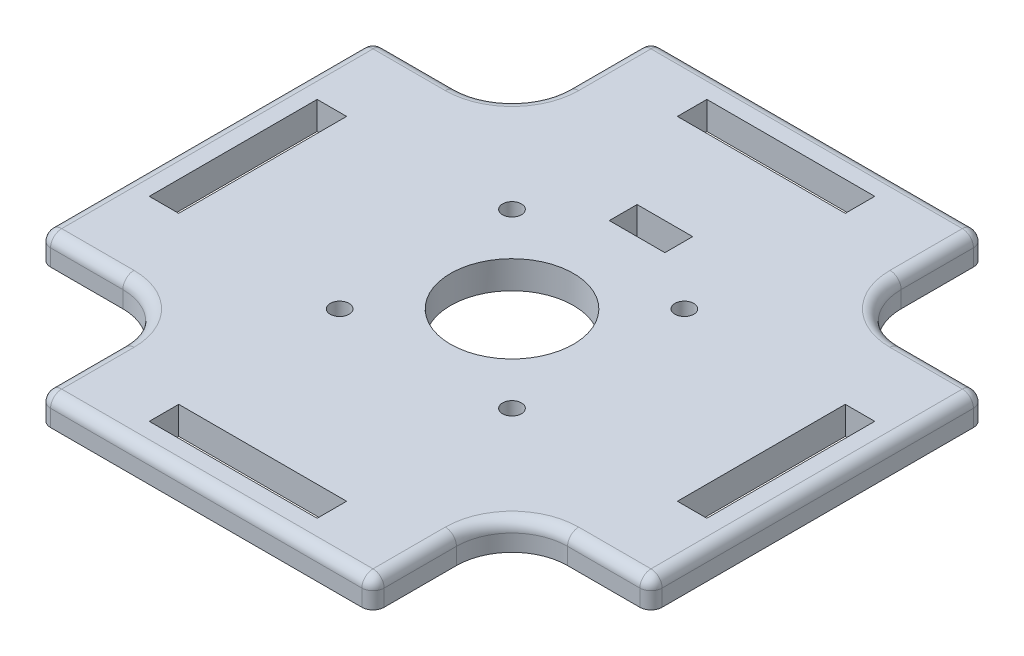
SolidWorks part; units mm, degrees
ref_plane "Płaszczyzna przednia" through (0, 0, 0) normal (0, 0, 1) x (1, 0, 0)
ref_plane "Płaszczyzna górna" through (0, 0, 0) normal (0, 1, 0) x (1, 0, 0)
ref_plane "Płaszczyzna prawa" through (0, 0, 0) normal (1, 0, 0) x (0, 0, -1)
sketch "Sketch1" plane through (0, 0, 0) normal (0, 1, 0) x (1, 0, 0)
  line L0 (-30, 55) -> (30, 55)
  line L1 (30, 55) -> (30, 30)
  line L2 (30, 30) -> (55, 30)
  line L3 (55, 30) -> (55, -30)
  line L4 (55, -30) -> (30, -30)
  line L5 (30, -30) -> (30, -55)
  line L6 (30, -55) -> (-30, -55)
  line L7 (-30, -55) -> (-30, -30)
  line L8 (-30, -30) -> (-55, -30)
  line L9 (-55, -30) -> (-55, 30)
  line L10 (-55, 30) -> (-30, 30)
  line L11 (-30, 30) -> (-30, 55)
  line L12 (0, 55) -> (0, -55) construction
  line L13 (-55, 0) -> (55, 0) construction
  point P14 (0, 0)
  point P18 (0, 0)
  dimension "D1" = 60
  dimension "D2" = 110
  dimension "D3" = 110
  dimension "D4" = 60
extrude "Boss-Extrude1" add sketch "Sketch1" along normal blind 5
sketch "Sketch2" plane through (0, 5, 0) normal (0, 1, 0) x (1, 0, 0)
  line L0 (-55, 0) -> (55, 0) construction
  line L1 (-55, 30) -> (-55, -30) construction
  line L2 (55, -30) -> (55, 30) construction
  line L3 (0, 55) -> (0, -55) construction
  line L4 (30, 55) -> (-30, 55) construction
  line L5 (-30, -55) -> (30, -55) construction
  line L7 (-44.85, -15.1) -> (-50.15, -15.1)
  line L8 (-44.85, -15.1) -> (-44.85, 15.1)
  line L9 (-44.85, 15.1) -> (-50.15, 15.1)
  line L10 (-50.15, -15.1) -> (-50.15, 15.1)
  line L11 (-44.85, -15.1) -> (-50.15, 15.1) construction
  line L12 (-44.85, 15.1) -> (-50.15, -15.1) construction
  circle A0 centre (0, 0) radius 11.05
  point P15 (-47.5, 0)
  dimension "D1" = 22.1
  dimension "D2" = 30.2
  dimension "D3" = 5.3
  dimension "D4" = 47.5
extrude "Cut-Extrude1" cut sketch "Sketch2" against normal up to next
pattern_circular "CirPattern1" count 4 over 360 about axis through (0, 0, 0) along (0, 1, 0) of "Cut-Extrude1"
sketch "Sketch5" plane through (0, 0, 0) normal (0, -1, 0) x (1, 0, 0)
  line L1 (15.5, -15.5) -> (-15.5, -15.5) construction
  line L2 (15.5, -15.5) -> (15.5, 15.5) construction
  line L3 (15.5, 15.5) -> (-15.5, 15.5) construction
  line L4 (-15.5, -15.5) -> (-15.5, 15.5) construction
  line L5 (15.5, -15.5) -> (-15.5, 15.5) construction
  line L6 (15.5, 15.5) -> (-15.5, -15.5) construction
  point P0 (0, 0)
  dimension "D1" = 31
hole_wizard "CBORE for M3 Hex Socket Thin Head Cap Screw1" positions "3DSketch2" profile "Sketch4" counterbore size "M3" standard "DIN" end condition through all
sketch3d "3DSketch2"
  line L0 (15.5, 0, -15.5) -> (-15.5, 0, 15.5) construction
  point P0 (-15.5, 0, 15.5)
  point P3 (-15.5, 0, -15.5)
  point P6 (15.5, 0, -15.5)
  point P9 (15.5, 0, 15.5)
sketch "Sketch4" plane through (-15.5, 0, 15.5) normal (1, 0, 0) x (0, 0, -1)
  line L0 (0, 0) -> (0, 5)
  line L1 (0, 5) -> (1.7, 5)
  line L3 (1.7, 5) -> (1.7, 2.4)
  line L4 (1.7, 2.4) -> (3.25, 2.4)
  line L5 (3.25, 2.4) -> (3.25, 0)
  line L7 (3.25, 0) -> (0, 0)
  line L11 (0, -6.35) -> (0, 107.95) construction
  dimension "Thru Hole Dia." = 3.4
  dimension "Thru Hole Depth" = 5
  dimension "C'Bore Dia." = 6.5
  dimension "C'Bore Depth" = 2.4
fillet "Fillet1" radius 10 4 edges at (-30, 2.5, -30) (30, 2.5, -30) (30, 2.5, 30) (-30, 2.5, 30)
fillet "Fillet2" radius 2 8 edges at (-55, 2.5, -30) (-30, 2.5, 55) (-55, 2.5, 30) (55, 2.5, 30) (30, 2.5, 55) (30, 2.5, -55) (55, 2.5, -30) (-30, 2.5, -55)
fillet "Fillet3" radius 2 24 edges at (-29.4142, 5, -54.4142) (0, 5, -55) (29.4142, 5, -54.4142) (30, 5, -46.5) (32.9289, 5, -32.9289) (46.5, 5, -30) (54.4142, 5, -29.4142) (55, 5, 0) (54.4142, 5, 29.4142) (46.5, 5, 30) (32.9289, 5, 32.9289) (30, 5, 46.5) (29.4142, 5, 54.4142) (0, 5, 55) (-29.4142, 5, 54.4142) (-30, 5, 46.5) (-32.9289, 5, 32.9289) (-46.5, 5, 30) (-54.4142, 5, 29.4142) (-55, 5, 0) (-54.4142, 5, -29.4142) (-46.5, 5, -30) (-32.9289, 5, -32.9289) (-30, 5, -46.5)
sketch "Sketch6" plane through (0, 5, 0) normal (0, 1, 0) x (1, 0, 0)
  line L1 (-5, 27.5) -> (5, 27.5)
  line L2 (-5, 27.5) -> (-5, 22.5)
  line L3 (-5, 22.5) -> (5, 22.5)
  line L4 (5, 27.5) -> (5, 22.5)
  line L5 (-5, 27.5) -> (5, 22.5) construction
  line L6 (-5, 22.5) -> (5, 27.5) construction
  point P0 (0, 25)
  dimension "D1" = 10
  dimension "D2" = 5
  dimension "D3" = 25
extrude "Cut-Extrude2" cut sketch "Sketch6" against normal up to next
